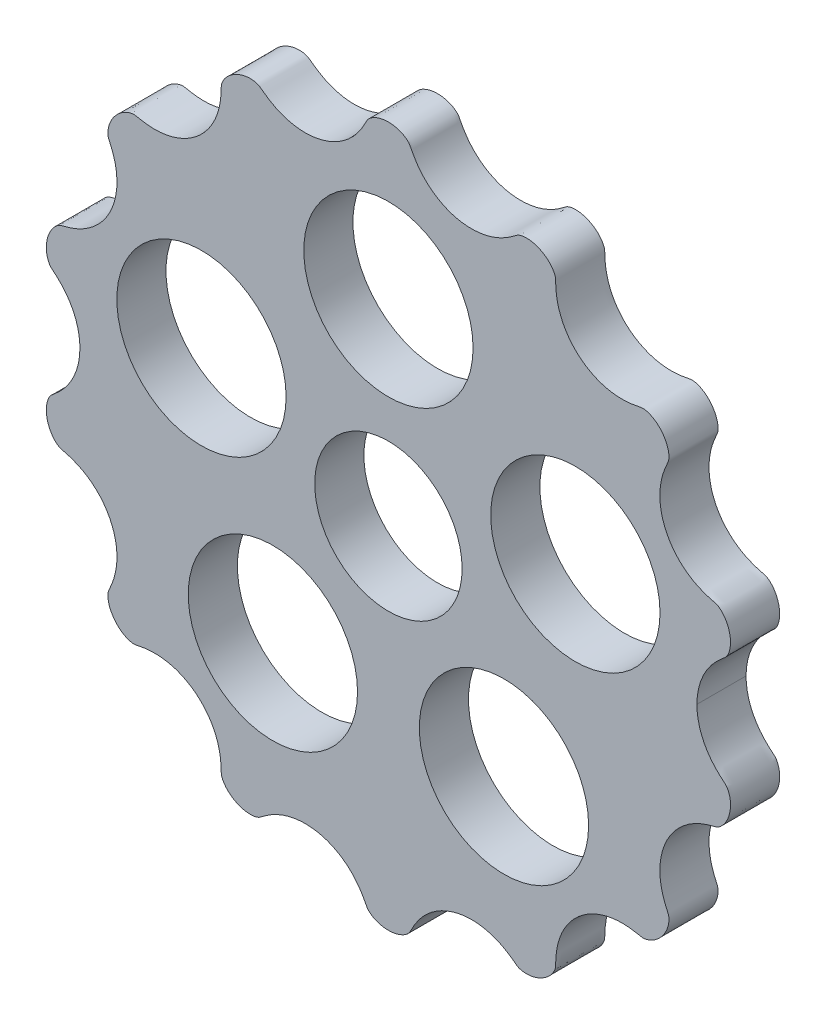
SolidWorks part; units mm, degrees
ref_plane "Front Plane" through (0, 0, 0) normal (0, 0, 1) x (1, 0, 0)
ref_plane "Top Plane" through (0, 0, 0) normal (0, 1, 0) x (1, 0, 0)
ref_plane "Right Plane" through (0, 0, 0) normal (1, 0, 0) x (0, 0, -1)
sketch "Sketch1" plane through (0, 0, 0) normal (0, 0, 1) x (1, 0, 0)
  line L0 (0, 0) -> (-50000, 0) construction
  spline S0 degree 4 poles (29.1148, 12.3034) (29.2251, 12.1678) (29.4552, 11.9043) (29.8276, 11.5337) (30.3727, 11.0937) (30.9601, 10.7121) (31.5053, 10.4321) (31.9903, 10.2313) (32.3732, 10.0998) (32.6459, 10.0172) (32.8897, 9.9508) (33.0761, 9.9023) (33.2365, 9.8624) (33.3649, 9.8232) (33.4599, 9.7833) (33.5683, 9.724) (33.7097, 9.6282) (33.879, 9.4852) (34.0743, 9.2772) (34.2676, 9.0162) (34.4376, 8.7246) (34.5807, 8.4046) (34.6855, 8.0862) (34.7563, 7.7736) (34.7922, 7.5075) (34.8058, 7.2895) (34.8069, 7.1092) (34.8014, 6.9663) (34.7862, 6.7987) (34.7706, 6.683) (34.7382, 6.5037) (34.7005, 6.3555) (34.6486, 6.1898) (34.5809, 6.02) (34.5049, 5.8706) (34.4228, 5.7426) (34.3425, 5.6471) (34.2725, 5.5788) (34.187, 5.5045) (34.0883, 5.422) (33.948, 5.3031) (33.7671, 5.1466) (33.5612, 4.9581) (33.2773, 4.6773) (32.9556, 4.3212) (32.6118, 3.8785) (32.2672, 3.3382) (31.9738, 2.7657) (31.7354, 2.1658) (31.5555, 1.5443) (31.4363, 0.9069) (31.3783, 0.2473) (31.3865, -0.4288) (31.4658, -1.1154) (31.6203, -1.8043) (31.8458, -2.4711) (32.1388, -3.1089) (32.4941, -3.7101) (32.8549, -4.1999) (33.1964, -4.5921) (33.4814, -4.8811) (33.6953, -5.0819) (33.8732, -5.2388) (34.0108, -5.3564) (34.1261, -5.4536) (34.2184, -5.5313) (34.3214, -5.6222) (34.4225, -5.7386) (34.5266, -5.9067) (34.6282, -6.1245) (34.7436, -6.4751) (34.8225, -6.9675) (34.8113, -7.5644) (34.661, -8.2417) (34.4218, -8.7837) (34.1503, -9.1912) (33.9029, -9.4619) (33.7187, -9.6221) (33.5394, -9.7456) (33.3669, -9.8285) (33.1823, -9.875) (33.0004, -9.9222) (32.782, -9.9793) (32.5292, -10.0512) (32.2433, -10.1425) (31.9268, -10.2589) (31.5377, -10.4223) (31.0835, -10.6476) (30.5742, -10.9541) (30.0282, -11.3617) (29.5242, -11.8241) (29.0684, -12.3375) (28.6707, -12.8905) (28.3339, -13.4763) (28.0598, -14.0888) (27.8495, -14.721) (27.7034, -15.3703) (27.6226, -16.0301) (27.6072, -16.6913) (27.6498, -17.2659) (27.7252, -17.7525) (27.8131, -18.1525) (27.8983, -18.4699) (27.9979, -18.7839) (28.1112, -19.094) (28.2196, -19.3578) (28.3162, -19.5777) (28.3886, -19.7384) (28.4347, -19.8413) (28.4769, -19.9459) (28.514, -20.0632) (28.5372, -20.2141) (28.546, -20.4211) (28.5287, -20.6643) (28.4793, -20.9385) (28.3904, -21.239) (28.2361, -21.6133) (27.9894, -22.0397) (27.6291, -22.4842) (27.199, -22.8485) (26.7944, -23.0902) (26.4653, -23.2258) (26.2334, -23.2927) (26.0388, -23.3257) (25.8855, -23.3344) (25.7494, -23.3208) (25.6312, -23.2987) (25.5035, -23.273) (25.3658, -23.2457) (25.1784, -23.2099) (24.8616, -23.1554) (24.425, -23.0993) (23.8669, -23.0674) (23.2277, -23.0884) (22.5933, -23.1683) (21.9654, -23.3085) (21.3502, -23.5092) (20.7566, -23.7687) (20.1904, -24.0849) (19.6475, -24.4614) (19.1353, -24.898) (18.6611, -25.3942) (18.2334, -25.9477) (17.8666, -26.541) (17.564, -27.1671) (17.3278, -27.818) (17.1796, -28.4029) (17.0935, -28.9116) (17.0509, -29.3082) (17.0309, -29.5904) (17.0202, -29.8431) (17.0147, -30.024) (17.0118, -30.1633) (17.0063, -30.2747) (16.9973, -30.3772) (16.9693, -30.5107) (16.9011, -30.6949) (16.7913, -30.9103) (16.5868, -31.2168) (16.2505, -31.5811) (15.7762, -31.9413) (15.1518, -32.2436) (14.5767, -32.3922) (14.0855, -32.431) (13.7189, -32.4031) (13.4803, -32.3569) (13.2942, -32.2977) (13.1612, -32.2347) (13.057, -32.1661) (12.9743, -32.1051) (12.872, -32.0278) (12.749, -31.9353) (12.5773, -31.8086) (12.354, -31.6518) (12.0257, -31.4379) (11.5814, -31.1844) (11.0404, -30.9303) (10.3942, -30.7013) (9.7255, -30.5379) (8.8696, -30.4195) (7.848, -30.4197) (6.8473, -30.5909) (5.9007, -30.9223) (5.1715, -31.2902) (4.6199, -31.6398) (4.1067, -32.0394) (3.6361, -32.4843) (3.2632, -32.9099) (2.973, -33.297) (2.7505, -33.6331) (2.6046, -33.8748) (2.4861, -34.0858) (2.3942, -34.2578) (2.3258, -34.3891) (2.2611, -34.5147) (2.1993, -34.6346) (2.1237, -34.762) (2.0189, -34.8849) (1.8703, -35.0205) (1.6749, -35.1617) (1.435, -35.2974) (1.1501, -35.4193) (0.7695, -35.5374) (0.2868, -35.6195) (-0.2046, -35.6253) (-0.6907, -35.5547) (-1.0776, -35.4449) (-1.3681, -35.3293) (-1.6139, -35.199) (-1.8161, -35.0628) (-1.9708, -34.931) (-2.084, -34.8131) (-2.1593, -34.7039) (-2.2091, -34.6147) (-2.2564, -34.5243) (-2.306, -34.4275) (-2.3668, -34.31) (-2.4588, -34.136) (-2.577, -33.9223) (-2.7226, -33.6774) (-2.945, -33.3365) (-3.2355, -32.9437) (-3.6093, -32.5119) (-4.0817, -32.0607) (-4.5974, -31.6554) (-5.1525, -31.3008) (-5.8873, -30.9274) (-6.8394, -30.5923) (-7.8448, -30.4197) (-8.8696, -30.4195) (-9.7255, -30.5379) (-10.3942, -30.7013) (-11.0404, -30.9303) (-11.5814, -31.1844) (-12.0257, -31.4379) (-12.354, -31.6518) (-12.5773, -31.8086) (-12.749, -31.9353) (-12.872, -32.0278) (-12.9743, -32.1051) (-13.057, -32.1661) (-13.1612, -32.2347) (-13.2942, -32.2977) (-13.4803, -32.3569) (-13.7189, -32.4031) (-14.0855, -32.431) (-14.5767, -32.3922) (-15.1518, -32.2436) (-15.7762, -31.9413) (-16.2505, -31.5811) (-16.5868, -31.2168) (-16.7913, -30.9103) (-16.9011, -30.6949) (-16.9693, -30.5107) (-16.9973, -30.3772) (-17.0063, -30.2747) (-17.0118, -30.1633) (-17.0147, -30.024) (-17.0202, -29.8431) (-17.0309, -29.5904) (-17.0509, -29.3082) (-17.0935, -28.9116) (-17.1796, -28.4029) (-17.3278, -27.818) (-17.564, -27.1671) (-17.8666, -26.541) (-18.2334, -25.9477) (-18.6611, -25.3942) (-19.1353, -24.898) (-19.6475, -24.4614) (-20.1904, -24.0849) (-20.7566, -23.7687) (-21.3502, -23.5092) (-21.9654, -23.3085) (-22.5933, -23.1683) (-23.2277, -23.0884) (-23.8669, -23.0674) (-24.425, -23.0993) (-24.8616, -23.1554) (-25.1784, -23.2099) (-25.3658, -23.2457) (-25.5035, -23.273) (-25.6312, -23.2987) (-25.7494, -23.3208) (-25.8855, -23.3344) (-26.0388, -23.3257) (-26.2334, -23.2927) (-26.4653, -23.2258) (-26.7944, -23.0902) (-27.199, -22.8485) (-27.6291, -22.4842) (-27.9894, -22.0397) (-28.2361, -21.6133) (-28.3904, -21.239) (-28.4793, -20.9385) (-28.5287, -20.6643) (-28.546, -20.4211) (-28.5372, -20.2141) (-28.514, -20.0632) (-28.4769, -19.9459) (-28.4347, -19.8413) (-28.3886, -19.7384) (-28.3162, -19.5777) (-28.2196, -19.3578) (-28.1112, -19.094) (-27.9979, -18.7839) (-27.8983, -18.4699) (-27.8131, -18.1525) (-27.7252, -17.7525) (-27.6498, -17.2659) (-27.6072, -16.6913) (-27.6226, -16.0301) (-27.7034, -15.3703) (-27.8495, -14.721) (-28.0598, -14.0888) (-28.3339, -13.4763) (-28.6707, -12.8905) (-29.0684, -12.3375) (-29.5242, -11.8241) (-30.0282, -11.3617) (-30.5742, -10.9541) (-31.0835, -10.6476) (-31.5377, -10.4223) (-31.9268, -10.2589) (-32.2433, -10.1425) (-32.5292, -10.0512) (-32.782, -9.9793) (-33.0004, -9.9222) (-33.1823, -9.875) (-33.3669, -9.8285) (-33.5394, -9.7456) (-33.7187, -9.6221) (-33.9029, -9.4619) (-34.1503, -9.1912) (-34.4218, -8.7837) (-34.661, -8.2417) (-34.8113, -7.5644) (-34.8225, -6.9675) (-34.7436, -6.4751) (-34.6282, -6.1245) (-34.5266, -5.9067) (-34.4225, -5.7386) (-34.3214, -5.6222) (-34.2184, -5.5313) (-34.1261, -5.4536) (-34.0108, -5.3564) (-33.8732, -5.2388) (-33.6953, -5.0819) (-33.4814, -4.8811) (-33.1964, -4.5921) (-32.8549, -4.1999) (-32.4941, -3.7101) (-32.1388, -3.1089) (-31.8458, -2.4711) (-31.6203, -1.8043) (-31.4658, -1.1154) (-31.3865, -0.4288) (-31.3783, 0.2473) (-31.4363, 0.9069) (-31.5555, 1.5443) (-31.7354, 2.1658) (-31.9738, 2.7657) (-32.2672, 3.3382) (-32.6118, 3.8785) (-32.9556, 4.3212) (-33.2773, 4.6773) (-33.5612, 4.9581) (-33.7671, 5.1466) (-33.948, 5.3031) (-34.0883, 5.422) (-34.187, 5.5045) (-34.2725, 5.5788) (-34.3425, 5.6471) (-34.4228, 5.7426) (-34.5049, 5.8706) (-34.5809, 6.02) (-34.6486, 6.1898) (-34.7005, 6.3555) (-34.7382, 6.5037) (-34.7706, 6.683) (-34.7862, 6.7987) (-34.8014, 6.9663) (-34.8069, 7.1092) (-34.8058, 7.2895) (-34.7922, 7.5075) (-34.7563, 7.7736) (-34.6855, 8.0862) (-34.5807, 8.4046) (-34.4376, 8.7246) (-34.2676, 9.0162) (-34.0743, 9.2772) (-33.879, 9.4852) (-33.7097, 9.6282) (-33.5683, 9.724) (-33.4599, 9.7833) (-33.3649, 9.8232) (-33.2365, 9.8624) (-33.0761, 9.9023) (-32.8897, 9.9508) (-32.6459, 10.0172) (-32.3732, 10.0998) (-31.9903, 10.2313) (-31.5053, 10.4321) (-30.9601, 10.7121) (-30.3727, 11.0937) (-29.8276, 11.5337) (-29.4552, 11.9043) (-29.2251, 12.1678) (-29.1148, 12.3034) knots 0 0 0 0 0 0.004405 0.008809 0.013214 0.01762 0.022025 0.024227 0.02643 0.027817 0.029205 0.030592 0.031286 0.031979 0.032583 0.033187 0.034394 0.036274 0.038154 0.040358 0.042562 0.044765 0.046967 0.048794 0.050621 0.051534 0.052447 0.053361 0.054274 0.055285 0.056296 0.057308 0.058319 0.059613 0.060907 0.061522 0.062138 0.062754 0.06337 0.064374 0.065379 0.067388 0.069397 0.071406 0.075439 0.079471 0.083501 0.087531 0.091623 0.095714 0.099779 0.103843 0.108282 0.112722 0.117161 0.121601 0.125988 0.130375 0.134727 0.136903 0.13908 0.1406 0.14212 0.14288 0.14364 0.1444 0.14516 0.146336 0.147512 0.14936 0.151209 0.15561 0.160014 0.164295 0.16858 0.170438 0.172297 0.173509 0.174721 0.175908 0.177095 0.178282 0.179469 0.181593 0.183717 0.185841 0.187965 0.192223 0.19648 0.200793 0.205106 0.209428 0.213749 0.217927 0.222104 0.226307 0.23051 0.234668 0.238827 0.242946 0.245005 0.247065 0.249144 0.251223 0.253303 0.255382 0.256328 0.257274 0.257748 0.258221 0.259167 0.260371 0.261575 0.263436 0.265296 0.267377 0.269458 0.273617 0.277665 0.281712 0.283577 0.285441 0.286612 0.287783 0.288539 0.289296 0.290053 0.290809 0.291822 0.292834 0.294859 0.29891 0.302906 0.306903 0.310951 0.314999 0.319092 0.323184 0.327249 0.331314 0.335714 0.340113 0.344511 0.348908 0.353257 0.357607 0.361927 0.364088 0.366248 0.367652 0.369056 0.37046 0.370811 0.371162 0.371864 0.373051 0.374238 0.376092 0.377946 0.382309 0.386671 0.390993 0.395318 0.397173 0.399028 0.40023 0.401432 0.402078 0.402725 0.403371 0.404018 0.40531 0.406603 0.408748 0.410892 0.415181 0.419482 0.423784 0.42814 0.432496 0.441216 0.449419 0.453546 0.457674 0.461762 0.465851 0.469909 0.473968 0.476 0.478032 0.480064 0.48108 0.482096 0.482945 0.483794 0.484643 0.485492 0.486669 0.487847 0.489701 0.491555 0.493598 0.495641 0.499725 0.503848 0.50591 0.507972 0.509842 0.511712 0.512906 0.514101 0.514957 0.515814 0.516243 0.516671 0.517528 0.518553 0.519579 0.521629 0.52368 0.525731 0.529831 0.533932 0.538049 0.542166 0.546333 0.550501 0.558784 0.567504 0.57186 0.576216 0.580518 0.584819 0.589108 0.591252 0.593397 0.59469 0.595982 0.596629 0.597275 0.597922 0.598568 0.59977 0.600972 0.602827 0.604682 0.609007 0.613329 0.617691 0.622054 0.623908 0.625762 0.626949 0.628136 0.628838 0.629189 0.62954 0.630944 0.632348 0.633752 0.635912 0.638073 0.642393 0.646743 0.651092 0.655489 0.659887 0.664286 0.668686 0.672751 0.676816 0.680908 0.685001 0.689049 0.693097 0.697094 0.70109 0.705141 0.707166 0.708178 0.709191 0.709947 0.710704 0.711461 0.712217 0.713388 0.714559 0.716423 0.718288 0.722335 0.726383 0.730542 0.732623 0.734704 0.736564 0.738425 0.739629 0.740833 0.741779 0.742252 0.742726 0.743672 0.744618 0.746697 0.748777 0.750856 0.752935 0.754995 0.757054 0.761173 0.765332 0.76949 0.773693 0.777896 0.782073 0.786251 0.790572 0.794894 0.799207 0.80352 0.807777 0.812035 0.814159 0.816283 0.818407 0.820531 0.821718 0.822905 0.824092 0.825279 0.826491 0.827703 0.829562 0.83142 0.835705 0.839986 0.84439 0.848791 0.85064 0.852488 0.853664 0.85484 0.8556 0.85636 0.85712 0.85788 0.8594 0.86092 0.863097 0.865273 0.869625 0.874012 0.878399 0.882839 0.887278 0.891718 0.896157 0.900221 0.904286 0.908377 0.912469 0.916499 0.920529 0.924561 0.928594 0.930603 0.932612 0.934621 0.935626 0.93663 0.937246 0.937862 0.938478 0.939093 0.940387 0.941681 0.942692 0.943704 0.944715 0.945726 0.946639 0.947553 0.948466 0.949379 0.951206 0.953033 0.955235 0.957438 0.959642 0.961846 0.963726 0.965606 0.966813 0.967417 0.968021 0.968714 0.969408 0.970795 0.972183 0.97357 0.975773 0.977975 0.98238 0.986786 0.991191 0.995595 1 1 1 1 1 construction
  spline S1 degree 4 poles (31.3875, 0) (31.3875, -0.1914) (31.4016, -0.559) (31.4625, -1.1005) (31.6203, -1.8043) (31.8458, -2.4711) (32.1388, -3.1089) (32.4941, -3.7101) (32.8549, -4.1999) (33.1964, -4.5921) (33.4814, -4.8811) (33.6953, -5.0819) (33.8732, -5.2388) (34.0108, -5.3564) (34.1261, -5.4536) (34.2184, -5.5313) (34.3214, -5.6222) (34.4225, -5.7386) (34.5266, -5.9067) (34.6282, -6.1245) (34.7436, -6.4751) (34.8225, -6.9675) (34.8113, -7.5644) (34.661, -8.2417) (34.4218, -8.7837) (34.1503, -9.1912) (33.9029, -9.4619) (33.7187, -9.6221) (33.5394, -9.7456) (33.3669, -9.8285) (33.1823, -9.875) (33.0004, -9.9222) (32.782, -9.9793) (32.5292, -10.0512) (32.2433, -10.1425) (31.9268, -10.2589) (31.5377, -10.4223) (31.0835, -10.6476) (30.5742, -10.9541) (30.0282, -11.3617) (29.5242, -11.8241) (29.0684, -12.3375) (28.6707, -12.8905) (28.3339, -13.4763) (28.0598, -14.0888) (27.8495, -14.721) (27.7034, -15.3703) (27.6226, -16.0301) (27.6072, -16.6913) (27.6498, -17.2659) (27.7252, -17.7525) (27.8131, -18.1525) (27.8983, -18.4699) (27.9979, -18.7839) (28.1112, -19.094) (28.2196, -19.3578) (28.3162, -19.5777) (28.3886, -19.7384) (28.4347, -19.8413) (28.4769, -19.9459) (28.514, -20.0632) (28.5372, -20.2141) (28.546, -20.4211) (28.5287, -20.6643) (28.4793, -20.9385) (28.3904, -21.239) (28.2361, -21.6133) (27.9894, -22.0397) (27.6291, -22.4842) (27.199, -22.8485) (26.7944, -23.0902) (26.4653, -23.2258) (26.2334, -23.2927) (26.0388, -23.3257) (25.8855, -23.3344) (25.7494, -23.3208) (25.6312, -23.2987) (25.5035, -23.273) (25.3658, -23.2457) (25.1784, -23.2099) (24.8616, -23.1554) (24.425, -23.0993) (23.8669, -23.0674) (23.2277, -23.0884) (22.5933, -23.1683) (21.9654, -23.3085) (21.3502, -23.5092) (20.7566, -23.7687) (20.1904, -24.0849) (19.6475, -24.4614) (19.1353, -24.898) (18.6611, -25.3942) (18.2334, -25.9477) (17.8666, -26.541) (17.564, -27.1671) (17.3278, -27.818) (17.1796, -28.4029) (17.0935, -28.9116) (17.0509, -29.3082) (17.0309, -29.5904) (17.0202, -29.8431) (17.0147, -30.024) (17.0118, -30.1633) (17.0063, -30.2747) (16.9973, -30.3772) (16.9693, -30.5107) (16.9011, -30.6949) (16.7913, -30.9103) (16.5868, -31.2168) (16.2505, -31.5811) (15.7762, -31.9413) (15.1518, -32.2436) (14.5767, -32.3922) (14.0855, -32.431) (13.7189, -32.4031) (13.4803, -32.3569) (13.2942, -32.2977) (13.1612, -32.2347) (13.057, -32.1661) (12.9743, -32.1051) (12.872, -32.0278) (12.749, -31.9353) (12.5773, -31.8086) (12.354, -31.6518) (12.0257, -31.4379) (11.5814, -31.1844) (11.0404, -30.9303) (10.3942, -30.7013) (9.7255, -30.5379) (8.8696, -30.4195) (7.848, -30.4197) (6.8473, -30.5909) (5.9007, -30.9223) (5.1715, -31.2902) (4.6199, -31.6398) (4.1067, -32.0394) (3.6361, -32.4843) (3.2632, -32.9099) (2.973, -33.297) (2.7505, -33.6331) (2.6046, -33.8748) (2.4861, -34.0858) (2.3942, -34.2578) (2.3258, -34.3891) (2.2611, -34.5147) (2.1993, -34.6346) (2.1237, -34.762) (2.0189, -34.8849) (1.8703, -35.0205) (1.6749, -35.1617) (1.435, -35.2974) (1.1501, -35.4193) (0.7695, -35.5374) (0.2868, -35.6195) (-0.2046, -35.6253) (-0.6907, -35.5547) (-1.0776, -35.4449) (-1.3681, -35.3293) (-1.6139, -35.199) (-1.8161, -35.0628) (-1.9708, -34.931) (-2.084, -34.8131) (-2.1593, -34.7039) (-2.2091, -34.6147) (-2.2564, -34.5243) (-2.306, -34.4275) (-2.3668, -34.31) (-2.4588, -34.136) (-2.577, -33.9223) (-2.7226, -33.6774) (-2.945, -33.3365) (-3.2355, -32.9437) (-3.6093, -32.5119) (-4.0817, -32.0607) (-4.5974, -31.6554) (-5.1525, -31.3008) (-5.8873, -30.9274) (-6.8394, -30.5923) (-7.8448, -30.4197) (-8.8696, -30.4195) (-9.7255, -30.5379) (-10.3942, -30.7013) (-11.0404, -30.9303) (-11.5814, -31.1844) (-12.0257, -31.4379) (-12.354, -31.6518) (-12.5773, -31.8086) (-12.749, -31.9353) (-12.872, -32.0278) (-12.9743, -32.1051) (-13.057, -32.1661) (-13.1612, -32.2347) (-13.2942, -32.2977) (-13.4803, -32.3569) (-13.7189, -32.4031) (-14.0855, -32.431) (-14.5767, -32.3922) (-15.1518, -32.2436) (-15.7762, -31.9413) (-16.2505, -31.5811) (-16.5868, -31.2168) (-16.7913, -30.9103) (-16.9011, -30.6949) (-16.9693, -30.5107) (-16.9973, -30.3772) (-17.0063, -30.2747) (-17.0118, -30.1633) (-17.0147, -30.024) (-17.0202, -29.8431) (-17.0309, -29.5904) (-17.0509, -29.3082) (-17.0935, -28.9116) (-17.1796, -28.4029) (-17.3278, -27.818) (-17.564, -27.1671) (-17.8666, -26.541) (-18.2334, -25.9477) (-18.6611, -25.3942) (-19.1353, -24.898) (-19.6475, -24.4614) (-20.1904, -24.0849) (-20.7566, -23.7687) (-21.3502, -23.5092) (-21.9654, -23.3085) (-22.5933, -23.1683) (-23.2277, -23.0884) (-23.8669, -23.0674) (-24.425, -23.0993) (-24.8616, -23.1554) (-25.1784, -23.2099) (-25.3658, -23.2457) (-25.5035, -23.273) (-25.6312, -23.2987) (-25.7494, -23.3208) (-25.8855, -23.3344) (-26.0388, -23.3257) (-26.2334, -23.2927) (-26.4653, -23.2258) (-26.7944, -23.0902) (-27.199, -22.8485) (-27.6291, -22.4842) (-27.9894, -22.0397) (-28.2361, -21.6133) (-28.3904, -21.239) (-28.4793, -20.9385) (-28.5287, -20.6643) (-28.546, -20.4211) (-28.5372, -20.2141) (-28.514, -20.0632) (-28.4769, -19.9459) (-28.4347, -19.8413) (-28.3886, -19.7384) (-28.3162, -19.5777) (-28.2196, -19.3578) (-28.1112, -19.094) (-27.9979, -18.7839) (-27.8983, -18.4699) (-27.8131, -18.1525) (-27.7252, -17.7525) (-27.6498, -17.2659) (-27.6072, -16.6913) (-27.6226, -16.0301) (-27.7034, -15.3703) (-27.8495, -14.721) (-28.0598, -14.0888) (-28.3339, -13.4763) (-28.6707, -12.8905) (-29.0684, -12.3375) (-29.5242, -11.8241) (-30.0282, -11.3617) (-30.5742, -10.9541) (-31.0835, -10.6476) (-31.5377, -10.4223) (-31.9268, -10.2589) (-32.2433, -10.1425) (-32.5292, -10.0512) (-32.782, -9.9793) (-33.0004, -9.9222) (-33.1823, -9.875) (-33.3669, -9.8285) (-33.5394, -9.7456) (-33.7187, -9.6221) (-33.9029, -9.4619) (-34.1503, -9.1912) (-34.4218, -8.7837) (-34.661, -8.2417) (-34.8113, -7.5644) (-34.8225, -6.9675) (-34.7436, -6.4751) (-34.6282, -6.1245) (-34.5266, -5.9067) (-34.4225, -5.7386) (-34.3214, -5.6222) (-34.2184, -5.5313) (-34.1261, -5.4536) (-34.0108, -5.3564) (-33.8732, -5.2388) (-33.6953, -5.0819) (-33.4814, -4.8811) (-33.1964, -4.5921) (-32.8549, -4.1999) (-32.4941, -3.7101) (-32.1388, -3.1089) (-31.8458, -2.4711) (-31.5589, -1.6226) (-31.4275, -0.9114) (-31.3875, -0.3676) (-31.3875, 0) knots 0.103459 0.103459 0.103459 0.103459 0.103459 0.108282 0.112722 0.117161 0.121601 0.125988 0.130375 0.134727 0.136903 0.13908 0.1406 0.14212 0.14288 0.14364 0.1444 0.14516 0.146336 0.147512 0.14936 0.151209 0.15561 0.160014 0.164295 0.16858 0.170438 0.172297 0.173509 0.174721 0.175908 0.177095 0.178282 0.179469 0.181593 0.183717 0.185841 0.187965 0.192223 0.19648 0.200793 0.205106 0.209428 0.213749 0.217927 0.222104 0.226307 0.23051 0.234668 0.238827 0.242946 0.245005 0.247065 0.249144 0.251223 0.253303 0.255382 0.256328 0.257274 0.257748 0.258221 0.259167 0.260371 0.261575 0.263436 0.265296 0.267377 0.269458 0.273617 0.277665 0.281712 0.283577 0.285441 0.286612 0.287783 0.288539 0.289296 0.290053 0.290809 0.291822 0.292834 0.294859 0.29891 0.302906 0.306903 0.310951 0.314999 0.319092 0.323184 0.327249 0.331314 0.335714 0.340113 0.344511 0.348908 0.353257 0.357607 0.361927 0.364088 0.366248 0.367652 0.369056 0.37046 0.370811 0.371162 0.371864 0.373051 0.374238 0.376092 0.377946 0.382309 0.386671 0.390993 0.395318 0.397173 0.399028 0.40023 0.401432 0.402078 0.402725 0.403371 0.404018 0.40531 0.406603 0.408748 0.410892 0.415181 0.419482 0.423784 0.42814 0.432496 0.441216 0.449419 0.453546 0.457674 0.461762 0.465851 0.469909 0.473968 0.476 0.478032 0.480064 0.48108 0.482096 0.482945 0.483794 0.484643 0.485492 0.486669 0.487847 0.489701 0.491555 0.493598 0.495641 0.499725 0.503848 0.50591 0.507972 0.509842 0.511712 0.512906 0.514101 0.514957 0.515814 0.516243 0.516671 0.517528 0.518553 0.519579 0.521629 0.52368 0.525731 0.529831 0.533932 0.538049 0.542166 0.546333 0.550501 0.558784 0.567504 0.57186 0.576216 0.580518 0.584819 0.589108 0.591252 0.593397 0.59469 0.595982 0.596629 0.597275 0.597922 0.598568 0.59977 0.600972 0.602827 0.604682 0.609007 0.613329 0.617691 0.622054 0.623908 0.625762 0.626949 0.628136 0.628838 0.629189 0.62954 0.630944 0.632348 0.633752 0.635912 0.638073 0.642393 0.646743 0.651092 0.655489 0.659887 0.664286 0.668686 0.672751 0.676816 0.680908 0.685001 0.689049 0.693097 0.697094 0.70109 0.705141 0.707166 0.708178 0.709191 0.709947 0.710704 0.711461 0.712217 0.713388 0.714559 0.716423 0.718288 0.722335 0.726383 0.730542 0.732623 0.734704 0.736564 0.738425 0.739629 0.740833 0.741779 0.742252 0.742726 0.743672 0.744618 0.746697 0.748777 0.750856 0.752935 0.754995 0.757054 0.761173 0.765332 0.76949 0.773693 0.777896 0.782073 0.786251 0.790572 0.794894 0.799207 0.80352 0.807777 0.812035 0.814159 0.816283 0.818407 0.820531 0.821718 0.822905 0.824092 0.825279 0.826491 0.827703 0.829562 0.83142 0.835705 0.839986 0.84439 0.848791 0.85064 0.852488 0.853664 0.85484 0.8556 0.85636 0.85712 0.85788 0.8594 0.86092 0.863097 0.865273 0.869625 0.874012 0.878399 0.882839 0.887278 0.896541 0.896541 0.896541 0.896541 0.896541
  spline S2 degree 4 poles (31.3875, 0) (31.3875, 0.1914) (31.4016, 0.559) (31.4625, 1.1005) (31.6203, 1.8043) (31.8458, 2.4711) (32.1388, 3.1089) (32.4941, 3.7101) (32.8549, 4.1999) (33.1964, 4.5921) (33.4814, 4.8811) (33.6953, 5.0819) (33.8732, 5.2388) (34.0108, 5.3564) (34.1261, 5.4536) (34.2184, 5.5313) (34.3214, 5.6222) (34.4225, 5.7386) (34.5266, 5.9067) (34.6282, 6.1245) (34.7436, 6.4751) (34.8225, 6.9675) (34.8113, 7.5644) (34.661, 8.2417) (34.4218, 8.7837) (34.1503, 9.1912) (33.9029, 9.4619) (33.7187, 9.6221) (33.5394, 9.7456) (33.3669, 9.8285) (33.1823, 9.875) (33.0004, 9.9222) (32.782, 9.9793) (32.5292, 10.0512) (32.2433, 10.1425) (31.9268, 10.2589) (31.5377, 10.4223) (31.0835, 10.6476) (30.5742, 10.9541) (30.0282, 11.3617) (29.5242, 11.8241) (29.0684, 12.3375) (28.6707, 12.8905) (28.3339, 13.4763) (28.0598, 14.0888) (27.8495, 14.721) (27.7034, 15.3703) (27.6226, 16.0301) (27.6072, 16.6913) (27.6498, 17.2659) (27.7252, 17.7525) (27.8131, 18.1525) (27.8983, 18.4699) (27.9979, 18.7839) (28.1112, 19.094) (28.2196, 19.3578) (28.3162, 19.5777) (28.3886, 19.7384) (28.4347, 19.8413) (28.4769, 19.9459) (28.514, 20.0632) (28.5372, 20.2141) (28.546, 20.4211) (28.5287, 20.6643) (28.4793, 20.9385) (28.3904, 21.239) (28.2361, 21.6133) (27.9894, 22.0397) (27.6291, 22.4842) (27.199, 22.8485) (26.7944, 23.0902) (26.4653, 23.2258) (26.2334, 23.2927) (26.0388, 23.3257) (25.8855, 23.3344) (25.7494, 23.3208) (25.6312, 23.2987) (25.5035, 23.273) (25.3658, 23.2457) (25.1784, 23.2099) (24.8616, 23.1554) (24.425, 23.0993) (23.8669, 23.0674) (23.2277, 23.0884) (22.5933, 23.1683) (21.9654, 23.3085) (21.3502, 23.5092) (20.7566, 23.7687) (20.1904, 24.0849) (19.6475, 24.4614) (19.1353, 24.898) (18.6611, 25.3942) (18.2334, 25.9477) (17.8666, 26.541) (17.564, 27.1671) (17.3278, 27.818) (17.1796, 28.4029) (17.0935, 28.9116) (17.0509, 29.3082) (17.0309, 29.5904) (17.0202, 29.8431) (17.0147, 30.024) (17.0118, 30.1633) (17.0063, 30.2747) (16.9973, 30.3772) (16.9693, 30.5107) (16.9011, 30.6949) (16.7913, 30.9103) (16.5868, 31.2168) (16.2505, 31.5811) (15.7762, 31.9413) (15.1518, 32.2436) (14.5767, 32.3922) (14.0855, 32.431) (13.7189, 32.4031) (13.4803, 32.3569) (13.2942, 32.2977) (13.1612, 32.2347) (13.057, 32.1661) (12.9743, 32.1051) (12.872, 32.0278) (12.749, 31.9353) (12.5773, 31.8086) (12.354, 31.6518) (12.0257, 31.4379) (11.5814, 31.1844) (11.0404, 30.9303) (10.3942, 30.7013) (9.7255, 30.5379) (8.8696, 30.4195) (7.848, 30.4197) (6.8473, 30.5909) (5.9007, 30.9223) (5.1715, 31.2902) (4.6199, 31.6398) (4.1067, 32.0394) (3.6361, 32.4843) (3.2632, 32.9099) (2.973, 33.297) (2.7505, 33.6331) (2.6046, 33.8748) (2.4861, 34.0858) (2.3942, 34.2578) (2.3258, 34.3891) (2.2611, 34.5147) (2.1993, 34.6346) (2.1237, 34.762) (2.0189, 34.8849) (1.8703, 35.0205) (1.6749, 35.1617) (1.435, 35.2974) (1.1501, 35.4193) (0.7695, 35.5374) (0.2868, 35.6195) (-0.2046, 35.6253) (-0.6907, 35.5547) (-1.0776, 35.4449) (-1.3681, 35.3293) (-1.6139, 35.199) (-1.8161, 35.0628) (-1.9708, 34.931) (-2.084, 34.8131) (-2.1593, 34.7039) (-2.2091, 34.6147) (-2.2564, 34.5243) (-2.306, 34.4275) (-2.3668, 34.31) (-2.4588, 34.136) (-2.577, 33.9223) (-2.7226, 33.6774) (-2.945, 33.3365) (-3.2355, 32.9437) (-3.6093, 32.5119) (-4.0817, 32.0607) (-4.5974, 31.6554) (-5.1525, 31.3008) (-5.8873, 30.9274) (-6.8394, 30.5923) (-7.8448, 30.4197) (-8.8696, 30.4195) (-9.7255, 30.5379) (-10.3942, 30.7013) (-11.0404, 30.9303) (-11.5814, 31.1844) (-12.0257, 31.4379) (-12.354, 31.6518) (-12.5773, 31.8086) (-12.749, 31.9353) (-12.872, 32.0278) (-12.9743, 32.1051) (-13.057, 32.1661) (-13.1612, 32.2347) (-13.2942, 32.2977) (-13.4803, 32.3569) (-13.7189, 32.4031) (-14.0855, 32.431) (-14.5767, 32.3922) (-15.1518, 32.2436) (-15.7762, 31.9413) (-16.2505, 31.5811) (-16.5868, 31.2168) (-16.7913, 30.9103) (-16.9011, 30.6949) (-16.9693, 30.5107) (-16.9973, 30.3772) (-17.0063, 30.2747) (-17.0118, 30.1633) (-17.0147, 30.024) (-17.0202, 29.8431) (-17.0309, 29.5904) (-17.0509, 29.3082) (-17.0935, 28.9116) (-17.1796, 28.4029) (-17.3278, 27.818) (-17.564, 27.1671) (-17.8666, 26.541) (-18.2334, 25.9477) (-18.6611, 25.3942) (-19.1353, 24.898) (-19.6475, 24.4614) (-20.1904, 24.0849) (-20.7566, 23.7687) (-21.3502, 23.5092) (-21.9654, 23.3085) (-22.5933, 23.1683) (-23.2277, 23.0884) (-23.8669, 23.0674) (-24.425, 23.0993) (-24.8616, 23.1554) (-25.1784, 23.2099) (-25.3658, 23.2457) (-25.5035, 23.273) (-25.6312, 23.2987) (-25.7494, 23.3208) (-25.8855, 23.3344) (-26.0388, 23.3257) (-26.2334, 23.2927) (-26.4653, 23.2258) (-26.7944, 23.0902) (-27.199, 22.8485) (-27.6291, 22.4842) (-27.9894, 22.0397) (-28.2361, 21.6133) (-28.3904, 21.239) (-28.4793, 20.9385) (-28.5287, 20.6643) (-28.546, 20.4211) (-28.5372, 20.2141) (-28.514, 20.0632) (-28.4769, 19.9459) (-28.4347, 19.8413) (-28.3886, 19.7384) (-28.3162, 19.5777) (-28.2196, 19.3578) (-28.1112, 19.094) (-27.9979, 18.7839) (-27.8983, 18.4699) (-27.8131, 18.1525) (-27.7252, 17.7525) (-27.6498, 17.2659) (-27.6072, 16.6913) (-27.6226, 16.0301) (-27.7034, 15.3703) (-27.8495, 14.721) (-28.0598, 14.0888) (-28.3339, 13.4763) (-28.6707, 12.8905) (-29.0684, 12.3375) (-29.5242, 11.8241) (-30.0282, 11.3617) (-30.5742, 10.9541) (-31.0835, 10.6476) (-31.5377, 10.4223) (-31.9268, 10.2589) (-32.2433, 10.1425) (-32.5292, 10.0512) (-32.782, 9.9793) (-33.0004, 9.9222) (-33.1823, 9.875) (-33.3669, 9.8285) (-33.5394, 9.7456) (-33.7187, 9.6221) (-33.9029, 9.4619) (-34.1503, 9.1912) (-34.4218, 8.7837) (-34.661, 8.2417) (-34.8113, 7.5644) (-34.8225, 6.9675) (-34.7436, 6.4751) (-34.6282, 6.1245) (-34.5266, 5.9067) (-34.4225, 5.7386) (-34.3214, 5.6222) (-34.2184, 5.5313) (-34.1261, 5.4536) (-34.0108, 5.3564) (-33.8732, 5.2388) (-33.6953, 5.0819) (-33.4814, 4.8811) (-33.1964, 4.5921) (-32.8549, 4.1999) (-32.4941, 3.7101) (-32.1388, 3.1089) (-31.8458, 2.4711) (-31.5589, 1.6226) (-31.4275, 0.9114) (-31.3875, 0.3676) (-31.3875, 0) knots 0.103459 0.103459 0.103459 0.103459 0.103459 0.108282 0.112722 0.117161 0.121601 0.125988 0.130375 0.134727 0.136903 0.13908 0.1406 0.14212 0.14288 0.14364 0.1444 0.14516 0.146336 0.147512 0.14936 0.151209 0.15561 0.160014 0.164295 0.16858 0.170438 0.172297 0.173509 0.174721 0.175908 0.177095 0.178282 0.179469 0.181593 0.183717 0.185841 0.187965 0.192223 0.19648 0.200793 0.205106 0.209428 0.213749 0.217927 0.222104 0.226307 0.23051 0.234668 0.238827 0.242946 0.245005 0.247065 0.249144 0.251223 0.253303 0.255382 0.256328 0.257274 0.257748 0.258221 0.259167 0.260371 0.261575 0.263436 0.265296 0.267377 0.269458 0.273617 0.277665 0.281712 0.283577 0.285441 0.286612 0.287783 0.288539 0.289296 0.290053 0.290809 0.291822 0.292834 0.294859 0.29891 0.302906 0.306903 0.310951 0.314999 0.319092 0.323184 0.327249 0.331314 0.335714 0.340113 0.344511 0.348908 0.353257 0.357607 0.361927 0.364088 0.366248 0.367652 0.369056 0.37046 0.370811 0.371162 0.371864 0.373051 0.374238 0.376092 0.377946 0.382309 0.386671 0.390993 0.395318 0.397173 0.399028 0.40023 0.401432 0.402078 0.402725 0.403371 0.404018 0.40531 0.406603 0.408748 0.410892 0.415181 0.419482 0.423784 0.42814 0.432496 0.441216 0.449419 0.453546 0.457674 0.461762 0.465851 0.469909 0.473968 0.476 0.478032 0.480064 0.48108 0.482096 0.482945 0.483794 0.484643 0.485492 0.486669 0.487847 0.489701 0.491555 0.493598 0.495641 0.499725 0.503848 0.50591 0.507972 0.509842 0.511712 0.512906 0.514101 0.514957 0.515814 0.516243 0.516671 0.517528 0.518553 0.519579 0.521629 0.52368 0.525731 0.529831 0.533932 0.538049 0.542166 0.546333 0.550501 0.558784 0.567504 0.57186 0.576216 0.580518 0.584819 0.589108 0.591252 0.593397 0.59469 0.595982 0.596629 0.597275 0.597922 0.598568 0.59977 0.600972 0.602827 0.604682 0.609007 0.613329 0.617691 0.622054 0.623908 0.625762 0.626949 0.628136 0.628838 0.629189 0.62954 0.630944 0.632348 0.633752 0.635912 0.638073 0.642393 0.646743 0.651092 0.655489 0.659887 0.664286 0.668686 0.672751 0.676816 0.680908 0.685001 0.689049 0.693097 0.697094 0.70109 0.705141 0.707166 0.708178 0.709191 0.709947 0.710704 0.711461 0.712217 0.713388 0.714559 0.716423 0.718288 0.722335 0.726383 0.730542 0.732623 0.734704 0.736564 0.738425 0.739629 0.740833 0.741779 0.742252 0.742726 0.743672 0.744618 0.746697 0.748777 0.750856 0.752935 0.754995 0.757054 0.761173 0.765332 0.76949 0.773693 0.777896 0.782073 0.786251 0.790572 0.794894 0.799207 0.80352 0.807777 0.812035 0.814159 0.816283 0.818407 0.820531 0.821718 0.822905 0.824092 0.825279 0.826491 0.827703 0.829562 0.83142 0.835705 0.839986 0.84439 0.848791 0.85064 0.852488 0.853664 0.85484 0.8556 0.85636 0.85712 0.85788 0.8594 0.86092 0.863097 0.865273 0.869625 0.874012 0.878399 0.882839 0.887278 0.896541 0.896541 0.896541 0.896541 0.896541
extrude "Boss-Extrude1" add sketch "Sketch1" along normal blind 5
sketch "Sketch2" plane through (0, 0, 5) normal (0, 0, 1) x (1, 0, 0)
  circle A0 centre (0, 0) radius 7.5
  circle A1 centre (0, 20) radius 8.6125
  circle A2 centre (19.0211, 6.1803) radius 8.6125
  circle A3 centre (11.7557, -16.1803) radius 8.6125
  circle A4 centre (-11.7557, -16.1803) radius 8.6125
  circle A5 centre (-19.0211, 6.1803) radius 8.6125
  point P21 (0, 0)
  dimension "D1" = 15
  dimension "D2" = 17.225
  dimension "D3" = 20
  dimension "D4" = 5
extrude "Cut-Extrude1" cut sketch "Sketch2" against normal through all and the other way through all
equation "\"roller_radius\"= 6.5"
equation "\"eccentricity\"= \"roller_radius\" * 0.325"
equation "\"outer_radius\"= 40"
equation "\"eccentric_shaft_radius\"= 16"
equation "\"rotor_width\"= 10"
equation "\"housing_depth\"= 40"
equation "\"bottom_depth\"= 5"
equation "\"roller_bearing_OD\"= \"roller_radius\" * 2"
equation "\"roller_bearing_ID\"= 6"
equation "\"eccentric_bearing_ID\"= 6"
equation "\"eccentric_bearing_OD\"= 15"
equation "\"roller_bearing_height\"= 5"
equation "\"eccentric_bearing_height\"= 5"
equation "\"bottom_bearing_ID\"= 15"
equation "\"bottom_bearing_OD\"= 32"
equation "\"bottom_bearing_height\"= 9"
equation "\"distance_to_output_rotor_holes\"= 20"
equation "\"D1@Boss-Extrude1\"=\"roller_bearing_height\""
equation "\"D1@Sketch2\"=\"eccentric_bearing_OD\""
equation "\"D2@Sketch2\"=\"roller_bearing_OD\"+\"eccentricity\"*2"
equation "\"D3@Sketch2\"=\"distance_to_output_rotor_holes\""
